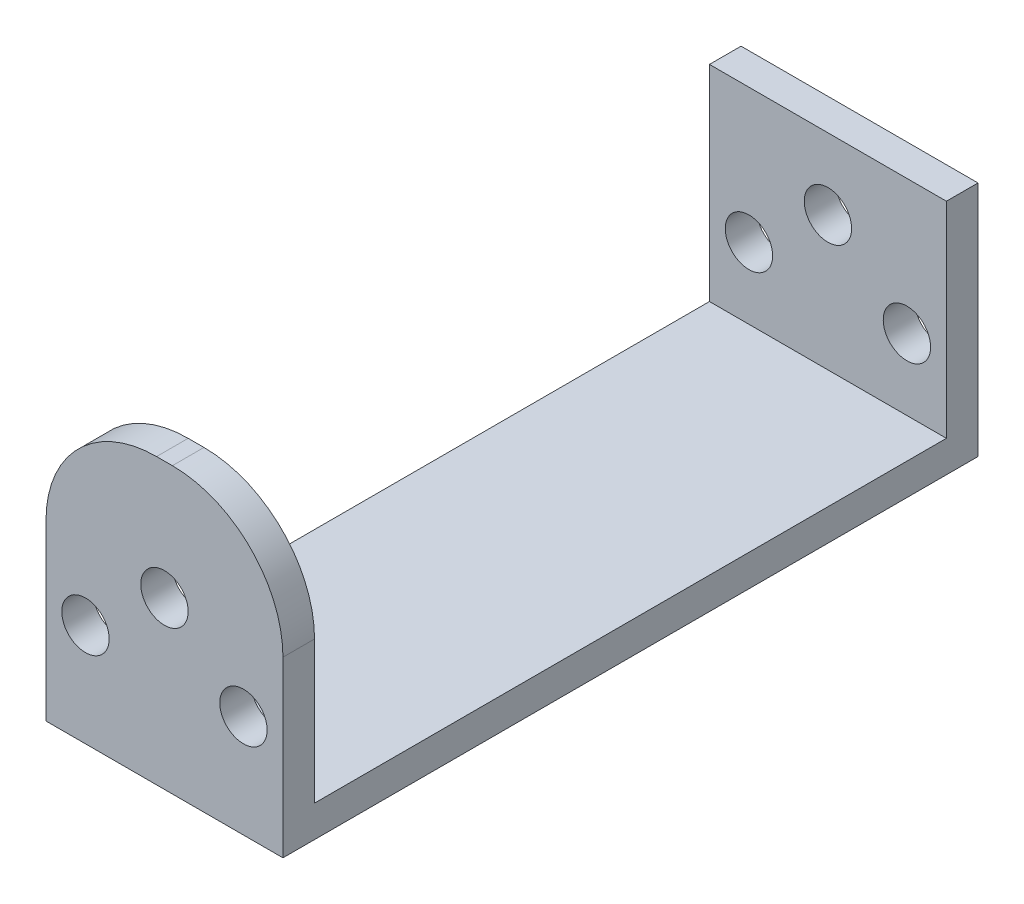
SolidWorks part; units mm, degrees
ref_plane "Alzado" through (0, 0, 0) normal (0, 0, 1) x (1, 0, 0)
ref_plane "Planta" through (0, 0, 0) normal (0, 1, 0) x (1, 0, 0)
ref_plane "Vista lateral" through (0, 0, 0) normal (1, 0, 0) x (0, 0, -1)
sketch "Croquis1" plane through (0, 0, 0) normal (1, 0, 0) x (0, 0, -1)
  line L0 (-22, 13) -> (-22, -2)
  line L1 (-20, 13) -> (20, 13) construction
  line L2 (-20, 13) -> (-20, 0)
  line L3 (-20, 0) -> (20, 0)
  line L4 (20, 13) -> (20, 0)
  line L5 (-22, -2) -> (22, -2)
  line L6 (22, 13) -> (22, -2)
  line L9 (20, 13) -> (22, 13)
  line L11 (-22, 15) -> (-22, -2) construction
  line L12 (-22, 15) -> (22, 15) construction
  line L13 (22, 15) -> (22, -2) construction
  line L14 (-20, 13) -> (-22, 13) construction
  line L15 (-20, 13) -> (-20, 16)
  line L16 (-20, 16) -> (-22, 16)
  line L17 (-22, 13) -> (-22, 16)
  point P4 (0, 0)
  dimension "D1" = 40
  dimension "D3" = 15
  dimension "D4" = 18
  dimension "D2" = 2
extrude "Saliente-Extruir1" add sketch "Croquis1" along normal mid plane 15
sketch "Croquis2" plane through (0, 0, 0) normal (0, 0, 1) x (1, 0, 0)
  line L0 (0, 8.5) -> (0, 0) construction
  line L1 (7.5, -2) -> (-7.5, -2) construction
  circle A0 centre (0, 8.5) radius 1.5
  circle A1 centre (5, 4.5) radius 1.5
  circle A2 centre (-5, 4.5) radius 1.5
  point P6 (0, 10)
  point P11 (0, 0)
  dimension "D1" = 3
  dimension "D2" = 3
  dimension "D5" = 10
  dimension "D3" = 12
  dimension "D4" = 4
extrude "Cortar-Extruir1" cut sketch "Croquis2" against normal through all both and the other way through all
fillet "Redondeo1" radius 7 2 edges at (7.5, 16, 21) (-7.5, 16, 21)
